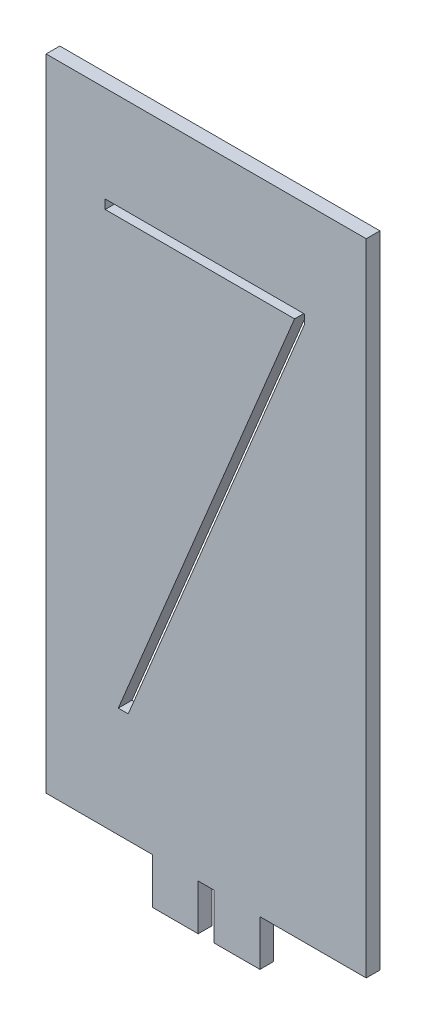
SolidWorks part; units mm, degrees
material "Glas"
ref_plane "Ebene vorne" through (0, 0, 0) normal (0, 0, 1) x (1, 0, 0)
ref_plane "Ebene oben" through (0, 0, 0) normal (0, 1, 0) x (1, 0, 0)
ref_plane "Ebene rechts" through (0, 0, 0) normal (1, 0, 0) x (0, 0, -1)
sketch "Skizze1" plane through (0, 0, 0) normal (0, 0, 1) x (1, 0, 0)
  line L1 (0, 0) -> (35, 0)
  line L2 (0, 0) -> (0, 75)
  line L3 (0, 75) -> (35, 75)
  line L4 (35, 0) -> (35, 75)
  dimension "D1" = 35
  dimension "D2" = 75
extrude "Aufsatz-Linear austragen1" add sketch "Skizze1" along normal blind 1.5
sketch "Skizze2" plane through (0, 0, 1.5) normal (0, 0, 1) x (1, 0, 0)
  line L0 (0, 0) -> (35, 0) construction
  line L1 (0, 0) -> (11.63, 0)
  line L2 (0, 0) -> (0, 5)
  line L3 (0, 5) -> (11.63, 5)
  line L4 (11.63, 0) -> (11.63, 5)
  line L5 (23.38, 5) -> (35, 5)
  line L6 (23.38, 5) -> (23.38, 0)
  line L7 (23.38, 0) -> (35, 0)
  line L8 (35, 5) -> (35, 0)
  line L9 (16.63, 0) -> (18.38, 0)
  line L10 (16.63, 0) -> (16.63, 5)
  line L11 (16.63, 5) -> (18.38, 5)
  line L12 (18.38, 0) -> (18.38, 5)
  dimension "D1" = 5
  dimension "D2" = 5
  dimension "D3" = 5
  dimension "D4" = 11.63
  dimension "D5" = 1.75
  dimension "D6" = 5
extrude "Schnitt-Linear austragen1" cut sketch "Skizze2" against normal blind 1.5
sketch "Skizze12" plane through (0, 0, 1.5) normal (0, 0, 1) x (1, 0, 0)
  line L0 (6.4592, 64.5) -> (28.25, 64.5)
  line L1 (28.25, 64.5) -> (28.25, 63.5)
  line L2 (28.25, 63.5) -> (8.9767, 17)
  line L3 (8.9767, 17) -> (7.8942, 17)
  line L4 (7.8942, 17) -> (27.1675, 63.5)
  line L5 (27.1675, 63.5) -> (6.4592, 63.5)
  line L6 (6.4592, 63.5) -> (6.4592, 64.5)
  line L7 (35, 75) -> (0, 75) construction
  line L8 (11.63, 5) -> (0, 5) construction
  line L10 (35, 5) -> (35, 75) construction
  dimension "D1" = 1
  dimension "D2" = 1
  dimension "D3" = 10.5
  dimension "D4" = 1
  dimension "D5" = 1
  dimension "D6" = 46.5
  dimension "D7" = 6.75
extrude "Schnitt-Linear austragen7" cut sketch "Skizze12" against normal blind 20
